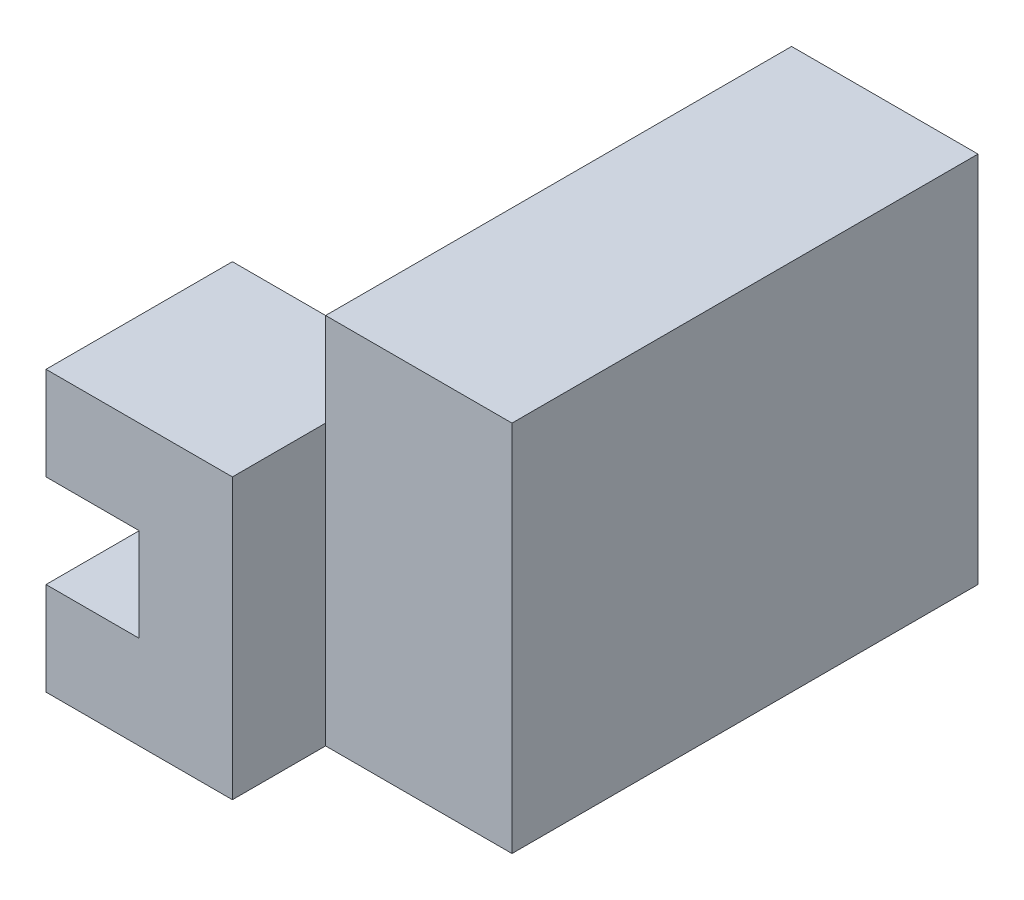
SolidWorks part; units mm, degrees
ref_plane "前基準面" through (0, 0, 0) normal (0, 0, 1) x (1, 0, 0)
ref_plane "上基準面" through (0, 0, 0) normal (0, 1, 0) x (1, 0, 0)
ref_plane "右基準面" through (0, 0, 0) normal (1, 0, 0) x (0, 0, -1)
sketch "草圖1" plane through (0, 0, 0) normal (0, 0, 1) x (1, 0, 0)
  line L0 (0, 0) -> (2, 0)
  line L1 (2, 0) -> (2, 4)
  line L2 (2, 4) -> (0, 4)
  line L3 (0, 4) -> (0, 0)
  dimension "D1" = 2
  dimension "D2" = 4
extrude "填料-伸長1" add sketch "草圖1" along normal blind 5
sketch "草圖3" plane through (0, 0, 0) normal (0, -1, 0) x (1, 0, 0)
  line L0 (0, 0) -> (-2, 0)
  line L1 (-2, 0) -> (-2, 5)
  line L2 (0, 5) -> (-2, 5)
  line L3 (0, 0) -> (0, 5)
  dimension "D1" = 2
  dimension "D2" = 5
extrude "填料-伸長2" add sketch "草圖3" against normal blind 1
sketch "草圖4" plane through (0, 0, 5) normal (0, 0, 1) x (1, 0, 0)
  line L0 (-1, 1) -> (-1, 2)
  line L1 (0, 1) -> (-2, 1) construction
  line L2 (-1, 2) -> (-2, 2)
  line L3 (-2, 2) -> (-2, 3)
  line L4 (-2, 3) -> (0, 3)
  line L5 (0, 4) -> (0, 1) construction
  line L6 (0, 3) -> (0, 0)
  line L7 (0, 0) -> (-2, 0)
  line L8 (-2, 0) -> (-2, 1)
  line L9 (-2, 1) -> (-1, 1)
  dimension "D1" = 1
  dimension "D2" = 1
extrude "填料-伸長3" add sketch "草圖4" along normal mid plane 2
